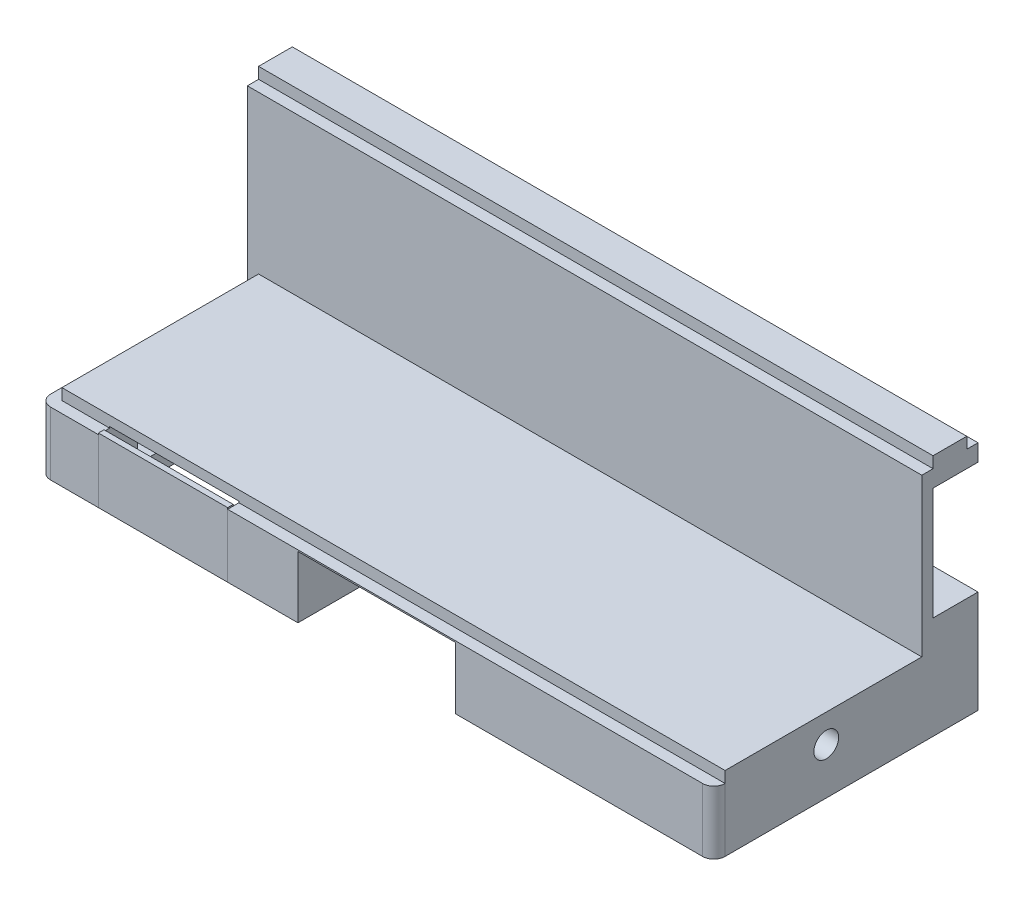
SolidWorks part; units mm, degrees
ref_plane "前视基准面" through (0, 0, 0) normal (0, 0, 1) x (1, 0, 0)
ref_plane "上视基准面" through (0, 0, 0) normal (0, 1, 0) x (1, 0, 0)
ref_plane "右视基准面" through (0, 0, 0) normal (1, 0, 0) x (0, 0, -1)
sketch "草图1" plane through (0, 0, 0) normal (0, 1, 0) x (1, 0, 0)
  line L1 (-614.5946, 325.1351) -> (-494.5946, 325.1351)
  line L2 (-614.5946, 325.1351) -> (-614.5946, 278.1351)
  line L3 (-614.5946, 278.1351) -> (-494.5946, 278.1351)
  line L4 (-494.5946, 325.1351) -> (-494.5946, 278.1351)
  dimension "D1" = 120
  dimension "D2" = 47
extrude "凸台-拉伸1" add sketch "草图1" along normal blind 15
sketch "草图2" plane through (0, 15, 0) normal (0, 1, 0) x (1, 0, 0)
  line L0 (-494.5946, 278.1351) -> (-494.5946, 325.1351) construction
  line L1 (-614.5946, 325.1351) -> (-494.5946, 325.1351)
  line L2 (-614.5946, 325.1351) -> (-614.5946, 315.1351)
  line L3 (-614.5946, 315.1351) -> (-494.5946, 315.1351)
  line L4 (-494.5946, 325.1351) -> (-494.5946, 315.1351)
  dimension "D1" = 10
extrude "凸台-拉伸2" add sketch "草图2" along normal blind 30
sketch "草图3" plane through (0, 0, -278.1351) normal (0, 0, 1) x (1, 0, 0)
  line L0 (-494.5946, 15) -> (-494.5946, 0) construction
  line L1 (-568.5946, 12.75) -> (-540.5946, 12.75)
  line L2 (-568.5946, 12.75) -> (-568.5946, 2.25)
  line L3 (-568.5946, 2.25) -> (-540.5946, 2.25)
  line L4 (-540.5946, 12.75) -> (-540.5946, 2.25)
  line L5 (-614.5946, 0) -> (-494.5946, 0) construction
  point P4 (-540.5946, 7.5)
  point P7 (-494.5946, 7.5)
  point P8 (-554.5946, 2.25)
  point P11 (-554.5946, 0)
  dimension "D1" = 0
  dimension "D2" = 0
extrude "切除-拉伸1" cut sketch "草图3" against normal through all
sketch "草图4" plane through (0, 0, -278.1351) normal (0, 0, 1) x (1, 0, 0)
  line L0 (-614.5946, 15) -> (-614.5946, 0) construction
  line L1 (-604.0946, 13.25) -> (-581.0946, 13.25)
  line L2 (-604.0946, 13.25) -> (-604.0946, 1.75)
  line L3 (-604.0946, 1.75) -> (-581.0946, 1.75)
  line L4 (-581.0946, 13.25) -> (-581.0946, 1.75)
  line L5 (-568.5946, 12.75) -> (-568.5946, 2.25) construction
  point P6 (-614.5946, 7.5)
  point P7 (-604.0946, 7.5)
  dimension "D1" = 0
  dimension "D2" = 12.5
  dimension "D3" = 23
  dimension "D4" = 11.5
extrude "切除-拉伸2" cut sketch "草图4" against normal through all
sketch "草图5" plane through (0, 0, -278.1351) normal (0, 0, 1) x (1, 0, 0)
  line L1 (-604.0946, 13.25) -> (-581.0946, 13.25)
  line L2 (-604.0946, 13.25) -> (-604.0946, 1.75)
  line L3 (-604.0946, 1.75) -> (-581.0946, 1.75)
  line L4 (-581.0946, 13.25) -> (-581.0946, 1.75)
extrude "凸台-拉伸3" add sketch "草图5" against normal blind 1 separate body
sketch "草图7" plane through (0, 0, -325.1351) normal (0, 0, -1) x (-1, 0, 0)
  line L0 (494.5946, 45) -> (494.5946, 0) construction
  line L1 (494.5946, 40) -> (509.5946, 40)
  line L2 (494.5946, 40) -> (494.5946, 20)
  line L3 (494.5946, 20) -> (509.5946, 20)
  line L4 (509.5946, 40) -> (509.5946, 37.8)
  line L5 (494.5946, 45) -> (614.5946, 45) construction
  line L7 (509.5946, 37.8) -> (579.5446, 37.8)
  line L9 (509.5946, 22.2) -> (531.1446, 22.2)
  line L12 (540.5946, 12.75) -> (604.0946, 12.75)
  line L13 (604.0946, 13.25) -> (604.0946, 1.75) construction
  line L14 (509.5946, 22.2) -> (509.5946, 20)
  line L15 (604.0946, 13.25) -> (604.0946, 12.75)
  arc A0 (540.5946, 12.75) -> (531.1446, 22.2) centre (531.1446, 12.75) ccw
  arc A2 (579.5446, 37.8) -> (604.0946, 13.25) centre (579.5446, 13.25) cw
  dimension "D7" = 9.45
  dimension "D1" = 5
  dimension "D2" = 5
  dimension "D3" = 15
  dimension "D4" = 2.2
  dimension "D5" = 2.2
extrude "切除-拉伸4" cut sketch "草图7" against normal blind 8
sketch "草图8" plane through (0, 0, -325.1351) normal (0, 0, -1) x (-1, 0, 0)
  line L0 (604.0946, 13.25) -> (604.0946, 1.75) construction
  line L1 (604.0946, 10) -> (608.0946, 10)
  line L2 (604.0946, 10) -> (604.0946, 5)
  line L3 (604.0946, 5) -> (608.0946, 5)
  line L4 (608.0946, 10) -> (608.0946, 5)
  line L5 (604.0946, 1.75) -> (581.0946, 1.75) construction
  line L6 (581.0946, 1.75) -> (581.0946, 12.75) construction
  line L7 (581.0946, 10) -> (577.0946, 10)
  line L8 (581.0946, 10) -> (581.0946, 5)
  line L9 (581.0946, 5) -> (577.0946, 5)
  line L10 (577.0946, 10) -> (577.0946, 5)
  dimension "D1" = 5
  dimension "D2" = 4
  dimension "D3" = 3.25
  dimension "D4" = 3.25
extrude "切除-拉伸5" cut sketch "草图8" against normal blind 40
sketch "草图9" plane through (0, 0, -325.1351) normal (0, 0, -1) x (-1, 0, 0)
  line L0 (568.5946, 2.25) -> (540.5946, 2.25) construction
  line L2 (546.7946, 2.25) -> (546.7946, 10.25)
  line L4 (562.3946, 2.25) -> (562.3946, 10.25)
  line L7 (494.5946, 20) -> (494.5946, 0) construction
  line L11 (546.7946, 2.25) -> (546.7946, 10.25)
  line L16 (562.3946, 2.25) -> (562.3946, 10.25)
  line L19 (568.5946, 12.75) -> (568.5946, 2.25) construction
  line L20 (546.7946, 2.25) -> (540.5946, 2.25)
  line L21 (546.7946, 2.25) -> (546.7946, 10.25)
  line L23 (540.5946, 2.25) -> (540.5946, 10.25)
  line L24 (562.3946, 2.25) -> (568.5946, 2.25)
  line L25 (562.3946, 2.25) -> (562.3946, 10.25)
  line L27 (568.5946, 2.25) -> (568.5946, 10.25)
  line L28 (546.7946, 10.25) -> (562.3946, 10.25)
  line L29 (540.5946, 10.25) -> (540.5946, 12.75)
  line L30 (540.5946, 12.75) -> (568.5946, 12.75)
  line L31 (568.5946, 10.25) -> (568.5946, 12.75)
  line M16 (568.5946, 12.75) -> (568.5946, 2.25)
  line M17 (568.5946, 2.25) -> (540.5946, 2.25)
  line M18 (540.5946, 2.25) -> (540.5946, 12.75)
  dimension "D1" = 15.6
  dimension "D2" = 8
  dimension "D3" = 52.2
  dimension "D4" = 6.2
  dimension "D5" = 6.2
  dimension "D6" = 2.5
extrude "凸台-拉伸5" add sketch "草图9" against normal blind 3 contours L30 L2 L28 L4 M18 M17 M16
fillet "圆角2" radius 2 4 edges at (-509.5946, 40, -321.1351) (-509.5946, 20, -321.1351) (-614.5946, 7.5, -278.1351) (-494.5946, 7.5, -278.1351)
sketch "草图10" plane through (0, 0, 0) normal (0, -1, 0) x (1, 0, 0)
  line L0 (-494.5946, -280.1351) -> (-494.5946, -325.1351) construction
  line L1 (-494.5946, -321.1351) -> (-544.5946, -321.1351)
  line L3 (-494.5946, -288.1351) -> (-544.5946, -288.1351)
  line L5 (-614.5946, -325.1351) -> (-614.5946, -280.1351) construction
  line L6 (-494.5946, -325.1351) -> (-614.5946, -325.1351) construction
  line L7 (-612.5946, -278.1351) -> (-496.5946, -278.1351) construction
  line L8 (-564.5946, -321.1351) -> (-614.5946, -321.1351)
  line L9 (-494.5946, -321.1351) -> (-544.5946, -321.1351)
  line L10 (-494.5946, -321.1351) -> (-494.5946, -325.1351)
  line L11 (-494.5946, -325.1351) -> (-614.5946, -325.1351)
  line L12 (-614.5946, -321.1351) -> (-614.5946, -325.1351)
  line L13 (-614.5946, -288.1351) -> (-564.5946, -288.1351)
  line L14 (-614.5946, -288.1351) -> (-614.5946, -278.1351)
  line L15 (-614.5946, -278.1351) -> (-494.5946, -278.1351)
  line L16 (-494.5946, -288.1351) -> (-494.5946, -278.1351)
  line L18 (-544.5946, -321.1351) -> (-544.5946, -288.1351)
  line L20 (-564.5946, -321.1351) -> (-564.5946, -288.1351)
  line L21 (-564.5946, -321.1351) -> (-614.5946, -321.1351)
  line L22 (-564.5946, -288.1351) -> (-614.5946, -288.1351)
  line L23 (-544.5946, -288.1351) -> (-494.5946, -288.1351)
  line L25 (-494.5946, -288.1351) -> (-514.5946, -288.1351)
  line L26 (-494.5946, -288.1351) -> (-494.5946, -280.1351)
  line L27 (-494.5946, -280.1351) -> (-514.5946, -280.1351)
  line L28 (-514.5946, -288.1351) -> (-514.5946, -280.1351)
  line L29 (-614.5946, -288.1351) -> (-594.5946, -288.1351)
  line L30 (-614.5946, -288.1351) -> (-614.5946, -280.1351)
  line L31 (-614.5946, -280.1351) -> (-594.5946, -280.1351)
  line L32 (-594.5946, -288.1351) -> (-594.5946, -280.1351)
  line L33 (-534.3675, -288.1351) -> (-574.3675, -288.1351)
  line L34 (-534.3675, -288.1351) -> (-534.3675, -280.1351)
  line L35 (-534.3675, -280.1351) -> (-574.3675, -280.1351)
  line L36 (-574.3675, -288.1351) -> (-574.3675, -280.1351)
  line M4 (-496.5946, -278.1351) -> (-612.5946, -278.1351)
  arc M5 (-612.5946, -278.1351) -> (-614.5946, -280.1351) centre (-612.5946, -280.1351) ccw
  line M6 (-614.5946, -280.1351) -> (-614.5946, -325.1351)
  line M7 (-614.5946, -325.1351) -> (-494.5946, -325.1351)
  line M8 (-494.5946, -325.1351) -> (-494.5946, -280.1351)
  arc M9 (-494.5946, -280.1351) -> (-496.5946, -278.1351) centre (-496.5946, -280.1351) ccw
  dimension "D1" = 4
  dimension "D2" = 10
  dimension "D3" = 10
  dimension "D4" = 50
  dimension "D5" = 50
  dimension "D6" = 20
  dimension "D7" = 2
  dimension "D8" = 8
extrude "凸台-拉伸6" add sketch "草图10" along normal blind 2 contours L20 L8 L1 L18 L3 L13 M6 M7 M8 M9 M4 M5
sketch "草图12" plane through (0, 45, 0) normal (0, 1, 0) x (1, 0, 0)
  line L0 (-494.5946, 315.1351) -> (-494.5946, 325.1351) construction
  line L1 (-614.5946, 325.1351) -> (-494.5946, 325.1351)
  line L2 (-614.5946, 325.1351) -> (-614.5946, 323.1351)
  line L3 (-614.5946, 323.1351) -> (-494.5946, 323.1351)
  line L4 (-494.5946, 325.1351) -> (-494.5946, 323.1351)
  line L6 (-614.5946, 315.1351) -> (-494.5946, 315.1351)
  line L7 (-614.5946, 315.1351) -> (-614.5946, 317.1351)
  line L8 (-614.5946, 317.1351) -> (-494.5946, 317.1351)
  line L9 (-494.5946, 315.1351) -> (-494.5946, 317.1351)
extrude "切除-拉伸7" cut sketch "草图12" against normal blind 2
sketch "草图15" plane through (0, 0, 0) normal (0, -1, 0) x (1, 0, 0)
  line L0 (-612.5946, -278.1351) -> (-496.5946, -278.1351) construction
  line L2 (-494.5946, -280.1351) -> (-494.5946, -321.1351) construction
  line L7 (-614.5946, -321.1351) -> (-614.5946, -280.1351) construction
  circle A1 centre (-574.5946, -283.1351) radius 2.2
  circle A2 centre (-534.5946, -283.1351) radius 2.2
  dimension "D1" = 4.4
  dimension "D3" = 5
  dimension "D2" = 4.4
  dimension "D6" = 40
  dimension "D4" = 5
  dimension "D5" = 40
extrude "切除-拉伸9" cut sketch "草图15" along direction (0, 1, 0) on the side against the normal blind 7
sketch "草图18" plane through (0, 0, -325.1351) normal (0, 0, -1) x (-1, 0, 0)
  line L1 (540.5946, 12.75) -> (604.0946, 12.75)
  line L2 (540.5946, 12.75) -> (540.5946, 1.75)
  line L3 (540.5946, 1.75) -> (604.0946, 1.75)
  line L4 (604.0946, 12.75) -> (604.0946, 1.75)
extrude "切除-拉伸15" cut sketch "草图18" against normal up to surface (8 mm away) up to face at (-535.7859, 24.7861, -317.1351)
sketch "草图20" plane through (0, 0, -317.1351) normal (0, 0, -1) x (-1, 0, 0)
  line L0 (581.0946, 1.75) -> (540.5946, 1.75) construction
  line L1 (540.5946, 2.25) -> (568.5946, 2.25)
  line L2 (540.5946, 2.25) -> (540.5946, 1.75)
  line L3 (540.5946, 1.75) -> (568.5946, 1.75)
  line L4 (568.5946, 2.25) -> (568.5946, 1.75)
extrude "切除-拉伸16" cut sketch "草图20" against normal blind 80
sketch "草图21" plane through (0, 0, -325.1351) normal (0, 0, -1) x (-1, 0, 0)
  line L0 (509.5946, 22.2) -> (531.1446, 22.2) construction
  line L1 (528.8578, 12.75) -> (528.8578, 1.75)
  line L4 (528.8578, 1.75) -> (540.5946, 1.75)
  line L5 (540.5946, 12.75) -> (540.5946, 1.75)
  line L6 (519.4078, 22.2) -> (531.1446, 22.2)
  arc A0 (528.8578, 12.75) -> (519.4078, 22.2) centre (519.4078, 12.75) ccw
  arc A1 (540.5946, 12.75) -> (531.1446, 22.2) centre (531.1446, 12.75) ccw construction
  arc A3 (540.5946, 12.75) -> (531.1446, 22.2) centre (531.1446, 12.75) ccw
  dimension "D1" = 9.45
extrude "切除-拉伸17" cut sketch "草图21" against normal up to surface (8 mm away) up to face at (-546.0881, 19.6271, -317.1351)
sketch "草图22" plane through (0, 0, -317.1351) normal (0, 0, -1) x (-1, 0, 0)
  line L1 (540.5946, 1.75) -> (528.8578, 1.75)
  line L2 (540.5946, 1.75) -> (540.5946, 12.75)
  line L3 (540.5946, 12.75) -> (528.8578, 12.75)
  line L4 (528.8578, 1.75) -> (528.8578, 12.75)
extrude "切除-拉伸18" cut sketch "草图22" against normal blind 25
sketch "草图24" plane through (0, -2, 0) normal (0, -1, 0) x (1, 0, 0)
  line L5 (-614.5946, -325.1351) -> (-494.5946, -325.1351)
  line L6 (-614.5946, -325.1351) -> (-614.5946, -321.1351)
  line L7 (-614.5946, -321.1351) -> (-494.5946, -321.1351)
  line L8 (-494.5946, -325.1351) -> (-494.5946, -321.1351)
extrude "切除-拉伸19" cut sketch "草图24" against normal up to surface (2 mm away) up to face at (-574.5946, 0, -285.3351)
sketch "草图25" plane through (0, -2, 0) normal (0, -1, 0) x (1, 0, 0)
  line L5 (-566.5252, -287.0142) -> (-543.24, -287.0142)
  line L6 (-566.5252, -287.0142) -> (-566.5252, -323.2017)
  line L7 (-566.5252, -323.2017) -> (-543.24, -323.2017)
  line L8 (-543.24, -287.0142) -> (-543.24, -323.2017)
extrude "切除-拉伸20" cut sketch "草图25" against normal up to surface (2 mm away) up to face at (-554.5946, 0, -294.3304)
sketch "草图27" plane through (0, 0, 0) normal (0, -1, 0) x (1, 0, 0)
  line L1 (-614.5946, -325.1351) -> (-493.9829, -325.1351)
  line L2 (-614.5946, -325.1351) -> (-614.5946, -274.6462)
  line L3 (-614.5946, -274.6462) -> (-493.9829, -274.6462)
  line L4 (-493.9829, -325.1351) -> (-493.9829, -274.6462)
extrude "切除-拉伸24" cut sketch "草图27" against normal up to surface (1.75 mm away) up to face at (-564.6472, 1.75, -298.1351)
sketch "草图28" plane through (0, 0, -317.1351) normal (0, 0, -1) x (-1, 0, 0)
  line L0 (579.5446, 37.8) -> (509.5946, 37.8) construction
  line L1 (525.5946, 37.8) -> (528.5946, 37.8)
  line L2 (525.5946, 37.8) -> (525.5946, 22.8)
  line L3 (525.5946, 22.8) -> (528.5946, 22.8)
  line L4 (528.5946, 37.8) -> (528.5946, 22.8)
  line L5 (494.5946, 40) -> (494.5946, 20) construction
  dimension "D1" = 15
  dimension "D2" = 3
  dimension "D3" = 31
extrude "凸台-拉伸7" add sketch "草图28" along normal blind 1.5
sketch "草图29" plane through (0, 15, 0) normal (0, 1, 0) x (1, 0, 0)
  line L0 (-614.5946, 315.1351) -> (-614.5946, 280.1351) construction
  line L1 (-494.5946, 280.1351) -> (-612.5946, 280.1351)
  line L2 (-494.5946, 280.1351) -> (-494.5946, 278.1351)
  line L3 (-494.5946, 278.1351) -> (-614.5946, 278.1351)
  line L4 (-614.5946, 280.1351) -> (-614.5946, 278.1351)
  line L5 (-614.5946, 315.1351) -> (-494.5946, 315.1351) construction
  line L7 (-614.5946, 280.1351) -> (-614.5946, 315.1351)
  line L8 (-614.5946, 315.1351) -> (-612.5946, 315.1351)
  line L9 (-612.5946, 280.1351) -> (-612.5946, 315.1351)
  dimension "D1" = 0
extrude "切除-拉伸25" cut sketch "草图29" against normal blind 2
sketch "草图30" plane through (0, 12.75, 0) normal (0, -1, 0) x (1, 0, 0)
  line L0 (-528.8578, -317.1351) -> (-568.5946, -317.1351) construction
  line L1 (-559.0946, -317.1351) -> (-550.0946, -317.1351)
  line L2 (-559.0946, -317.1351) -> (-559.0946, -309.1351)
  line L3 (-559.0946, -309.1351) -> (-550.0946, -309.1351)
  line L4 (-550.0946, -317.1351) -> (-550.0946, -309.1351)
  circle A0 centre (-554.5946, -313.1351) radius 2.2
  circle A1 centre (-574.5946, -283.1351) radius 2.2 construction
  dimension "D1" = 4.4
  dimension "D2" = 30
  dimension "D3" = 20
  dimension "D4" = 9
  dimension "D5" = 4.5
  dimension "D6" = 8
extrude "凸台-拉伸8" add sketch "草图30" along normal up to surface (11 mm away) up to face at (-534.5946, 1.75, -285.3351)
sketch "草图33" plane through (-494.5946, 0, 0) normal (1, 0, 0) x (0, 0, -1)
  line L0 (278.1351, 1.75) -> (278.1351, 13) construction
  line L1 (280.1351, 15) -> (315.1351, 15) construction
  circle A0 centre (298.1351, 10) radius 2.2
  dimension "D1" = 4.4
  dimension "D2" = 20
  dimension "D3" = 5
extrude "切除-拉伸27" cut sketch "草图33" against normal blind 5
